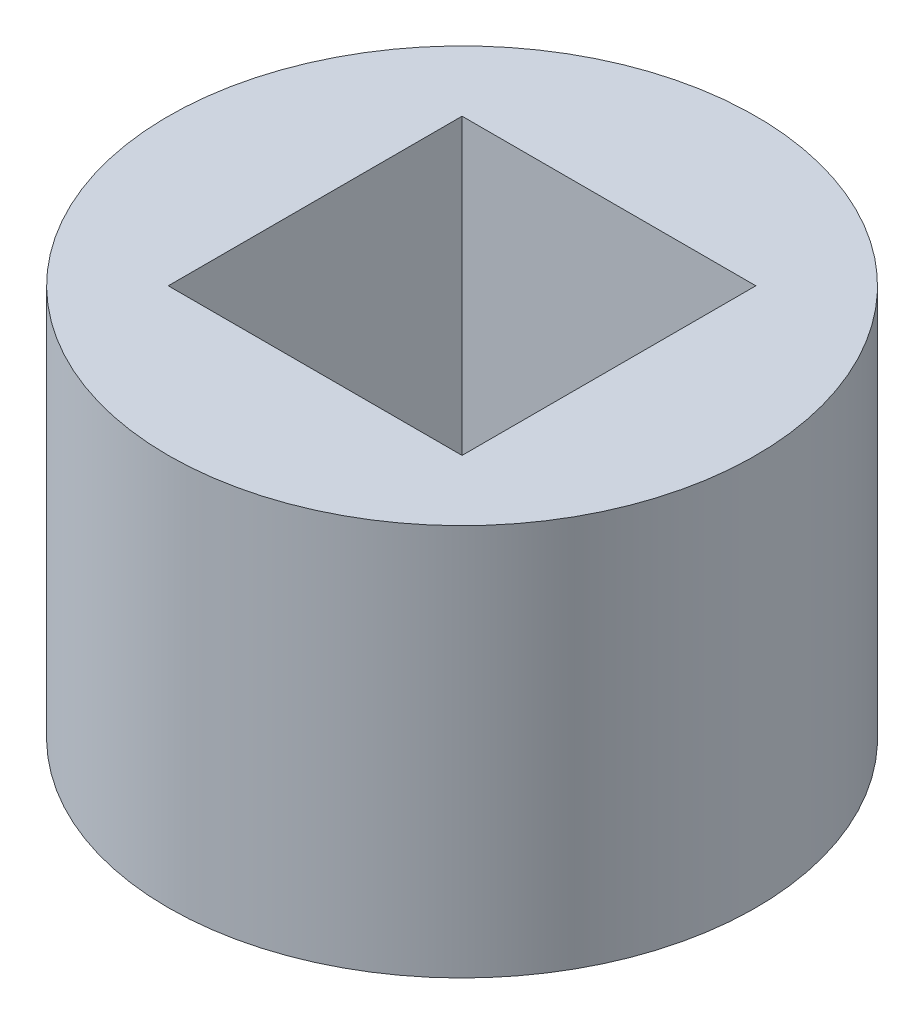
SolidWorks part; units mm, degrees
ref_plane "前视基准面" through (0, 0, 0) normal (0, 0, 1) x (1, 0, 0)
ref_plane "上视基准面" through (0, 0, 0) normal (0, 1, 0) x (1, 0, 0)
ref_plane "右视基准面" through (0, 0, 0) normal (1, 0, 0) x (0, 0, -1)
sketch "草图2" plane through (0, 0, 0) normal (0, 1, 0) x (1, 0, 0)
  line L1 (-7.5, 7.5) -> (7.5, 7.5)
  line L2 (-7.5, 7.5) -> (-7.5, -7.5)
  line L3 (-7.5, -7.5) -> (7.5, -7.5)
  line L4 (7.5, 7.5) -> (7.5, -7.5)
  line L5 (-7.5, 7.5) -> (7.5, -7.5) construction
  line L6 (-7.5, -7.5) -> (7.5, 7.5) construction
  circle A0 centre (0, 0) radius 15
  circle A1 centre (18.3824, 9.6496) radius 3.7803
  point P9 (-20.937, 17.8611)
  point P10 (-20.6531, 4.9441)
  point P11 (0, 0)
  point P12 (-22.2802, 18.6745)
  point P13 (18.9193, 17.4332)
  point P14 (14.6248, 23.5728)
  point P15 (18.3824, 15.5208)
  point P16 (18.3824, -3.9046)
  point P17 (0, 0)
  point P18 (18.3824, 9.6496)
  dimension "D1" = 30
  dimension "D3" = 7.5605
  dimension "D2" = 15
  dimension "D4" = 18.3824
  dimension "D5" = 9.6496
extrude "凸台-拉伸1" add sketch "草图2" along normal blind 20
